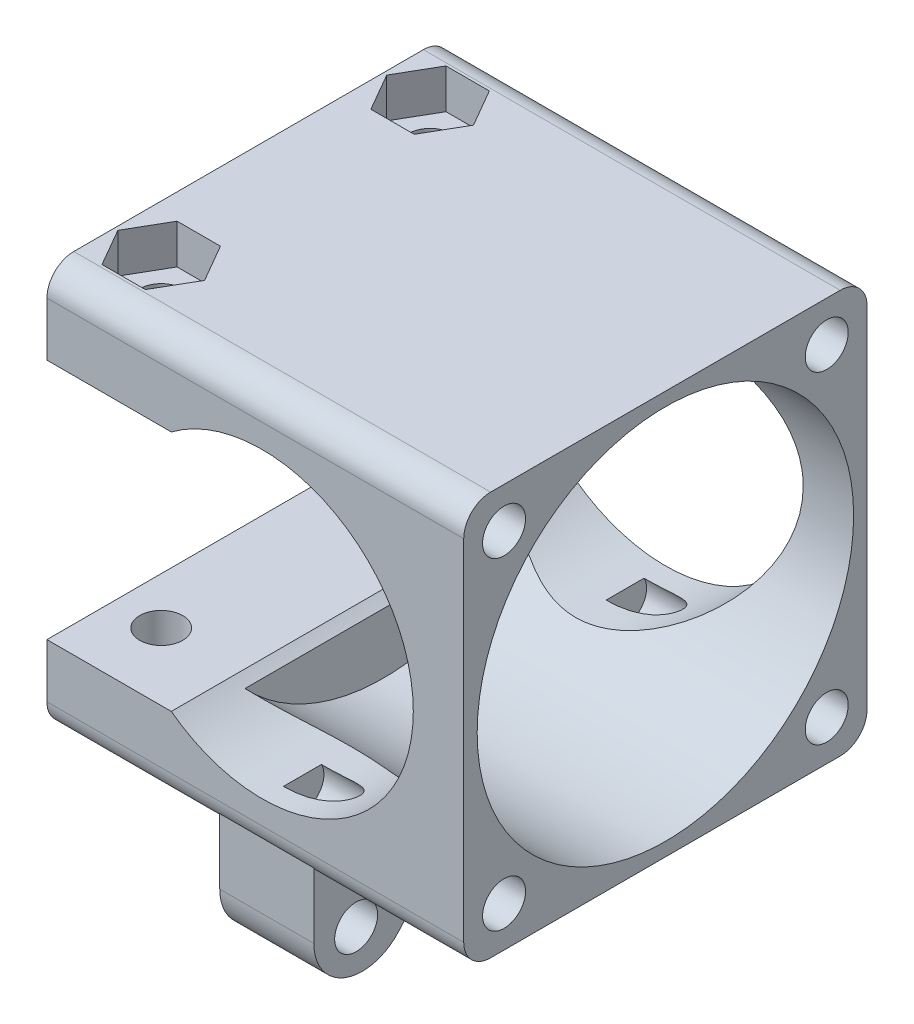
SolidWorks part; units mm, degrees
material "ABS"
ref_plane "Front Plane" through (0, 0, 0) normal (0, 0, 1) x (1, 0, 0)
ref_plane "Top Plane" through (0, 0, 0) normal (0, 1, 0) x (1, 0, 0)
ref_plane "Right Plane" through (0, 0, 0) normal (1, 0, 0) x (0, 0, -1)
sketch "Sketch1" plane through (0, 0, 0) normal (1, 0, 0) x (0, 0, -1)
  line L1 (-30, -15) -> (0, -15)
  line L2 (-30, -15) -> (-30, 15)
  line L3 (-30, 15) -> (0, 15)
  line L4 (0, -15) -> (0, 15)
  dimension "D1" = 30
  dimension "D2" = 30
extrude "Boss-Extrude1" add sketch "Sketch1" against normal mid plane 31
fillet "Fillet1" radius 2 4 edges at (0, 15, 0) (0, -15, 30) (0, -15, 0) (0, 15, 30)
sketch "Sketch2" plane through (15.5, 0, 0) normal (1, 0, 0) x (0, 0, -1)
  line L0 (-15, 15) -> (-15, -15) construction
  line L1 (-2, 15) -> (-28, 15) construction
  line L2 (-28, -15) -> (-2, -15) construction
  circle A0 centre (-15, 0) radius 14
  dimension "D1" = 28
extrude "Cut-Extrude1" cut sketch "Sketch2" against normal blind 21
sketch "Sketch3" plane through (15.5, 0, 0) normal (1, 0, 0) x (0, 0, -1)
  line L0 (-27, -12) -> (-27, 12) construction
  line L1 (-27, 12) -> (-3, 12) construction
  line L2 (-15, 12) -> (-15, 0) construction
  line L3 (-15, 0) -> (-27, 0) construction
  circle A0 centre (-27, 12) radius 1.6
  circle A1 centre (-3, 12) radius 1.6
  circle A2 centre (-3, -12) radius 1.6
  circle A3 centre (-27, -12) radius 1.6
  dimension "D1" = 3.2
  dimension "D2" = 24
extrude "Cut-Extrude2" cut sketch "Sketch3" against normal blind 15
sketch "Sketch4" plane through (0, 0, 30) normal (0, 0, 1) x (1, 0, 0)
  line L0 (-6.25, 9) -> (-15.5, 9)
  line L1 (-15.5, 13) -> (-15.5, -13) construction
  line L2 (-15.5, 9) -> (-15.5, -9)
  line L3 (-15.5, -9) -> (-6.25, -9)
  line L4 (15.5, 13) -> (15.5, -13) construction
  arc A0 (-6.25, -9) -> (-6.25, 9) centre (0.5, 0) ccw
  dimension "D1" = 11.25
  dimension "D2" = 15
  dimension "D3" = 18
extrude "Cut-Extrude3" cut sketch "Sketch4" against normal through all
sketch "Sketch5" plane through (0, 15, 0) normal (0, 1, 0) x (1, 0, 0)
  line L0 (-12, -5) -> (-12, -25) construction
  line L1 (-15.5, -15) -> (-12, -15) construction
  line L2 (-15.5, -2) -> (-15.5, -28) construction
  circle A0 centre (-12, -5) radius 1.6
  circle A1 centre (-12, -25) radius 1.6
  dimension "D1" = 3.2
  dimension "D2" = 20
  dimension "D3" = 3.5
extrude "Cut-Extrude4" cut sketch "Sketch5" against normal through all
sketch "Sketch6" plane through (0, 15, 0) normal (0, 1, 0) x (1, 0, 0)
  line L1 (-10.3873, -7.7933) -> (-8.7746, -5)
  line L2 (-8.7746, -5) -> (-10.3873, -2.2067)
  line L3 (-10.3873, -2.2067) -> (-13.6127, -2.2067)
  line L4 (-13.6127, -2.2067) -> (-15.2254, -5)
  line L5 (-15.2254, -5) -> (-13.6127, -7.7933)
  line L6 (-13.6127, -7.7933) -> (-10.3873, -7.7933)
  line L7 (-8.7746, -25) -> (-10.3873, -22.2067)
  line L8 (-10.3873, -22.2067) -> (-13.6127, -22.2067)
  line L9 (-13.6127, -22.2067) -> (-15.2254, -25)
  line L10 (-15.2254, -25) -> (-13.6127, -27.7933)
  line L11 (-13.6127, -27.7933) -> (-10.3873, -27.7933)
  line L12 (-10.3873, -27.7933) -> (-8.7746, -25)
  circle A0 centre (-12, -5) radius 2.7933 construction
  circle A1 centre (-12, -25) radius 2.7933 construction
  dimension "D1" = 5.5866
extrude "Cut-Extrude5" cut sketch "Sketch6" against normal blind 2.95
sketch "Sketch7" plane through (0, -15, 0) normal (0, -1, 0) x (1, 0, 0)
  circle A0 centre (-12, 25) radius 2.85
  circle A1 centre (-12, 5) radius 2.85
  dimension "D1" = 5.7
extrude "Cut-Extrude6" cut sketch "Sketch7" against normal blind 2.95
sketch "Sketch8" plane through (15.5, 0, 0) normal (1, 0, 0) x (0, 0, -1)
  line L0 (-29.6463, -14.1356) -> (-29.6463, -19)
  line L1 (-23.3681, -21.4057) -> (-17.6141, -15)
  line L2 (-28, -15) -> (-2, -15) construction
  line L3 (-17.6141, -15) -> (-28, -15)
  line L4 (-30, 13) -> (-30, -13) construction
  arc A0 (-29.6463, -19) -> (-23.3681, -21.4057) centre (-26.0463, -19) ccw
  arc A1 (-30, -13) -> (-28, -15) centre (-28, -13) ccw construction
  arc A2 (-29.6463, -14.1356) -> (-28, -15) centre (-28, -13) ccw
  dimension "D3" = 3.6
  dimension "D4" = 4
  dimension "D1" = 12.3859
  dimension "D2" = 0.3537
extrude "Boss-Extrude2" add sketch "Sketch8" against normal blind 7 from offset 11.5 offset against normal yes
sketch "Sketch9" plane through (4, 0, 0) normal (1, 0, 0) x (0, 0, -1)
  line L0 (-17.6141, -15) -> (-28, -15) construction
  line L1 (-30, 13) -> (-30, -13) construction
  circle A0 centre (-26.5, -19.5) radius 1.6
  dimension "D1" = 3.2
  dimension "D2" = 4.5
  dimension "D3" = 3.5
extrude "Cut-Extrude7" cut sketch "Sketch9" against normal through all
